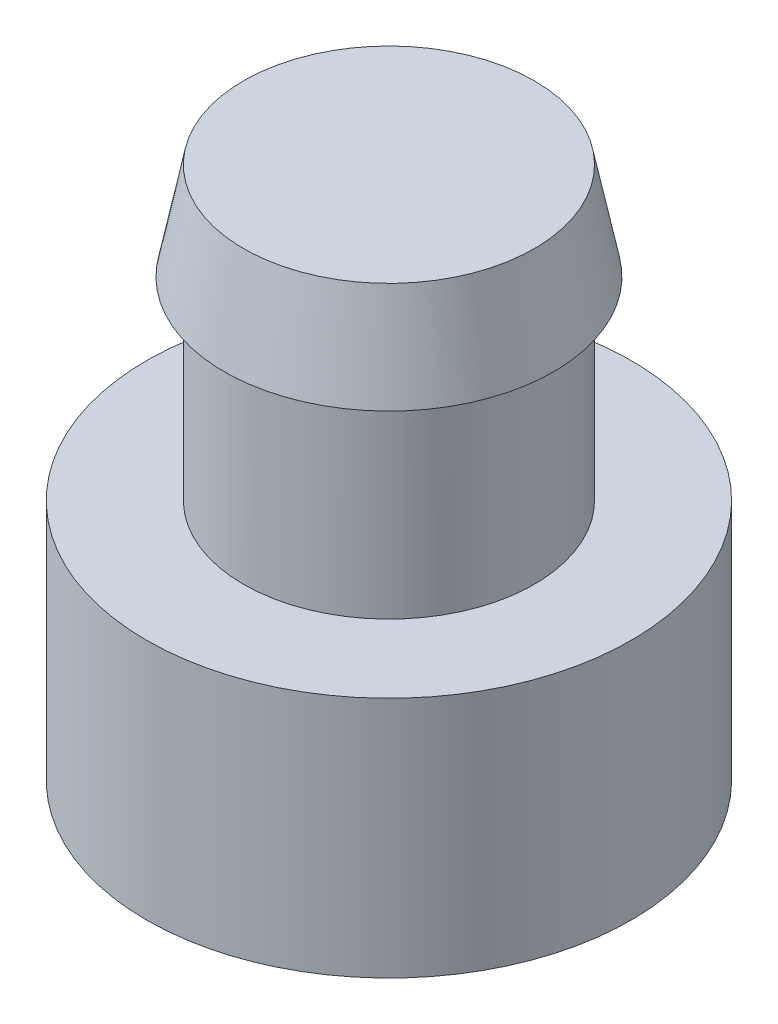
SolidWorks part; units mm, degrees
ref_plane "Front Plane" through (0, 0, 0) normal (0, 0, 1) x (1, 0, 0)
ref_plane "Top Plane" through (0, 0, 0) normal (0, 1, 0) x (1, 0, 0)
ref_plane "Right Plane" through (0, 0, 0) normal (1, 0, 0) x (0, 0, -1)
sketch "Sketch1" plane through (0, 0, 0) normal (0, 1, 0) x (1, 0, 0)
  circle A0 centre (0, 0) radius 2.5
  dimension "D1" = 5
extrude "Boss-Extrude1" add sketch "Sketch1" along normal blind 2.5
sketch "Sketch2" plane through (0, 2.5, 0) normal (0, 1, 0) x (1, 0, 0)
  circle A0 centre (0, 0) radius 1.5
  dimension "D1" = 3
extrude "Boss-Extrude2" add sketch "Sketch2" along normal blind 3
sketch "Sketch3" plane through (0, 0, 0) normal (0, 0, 1) x (1, 0, 0)
  line L0 (1.5, 5.5) -> (1.5, 4.5)
  line L1 (1.5, 2.5) -> (1.5, 5.5) construction
  line L2 (1.5, 4.5) -> (1.7, 4.5)
  line L3 (1.7, 4.5) -> (1.5, 5.5)
  line L4 (0, 0) -> (0, 5.5) construction
  line L5 (1.5, 5.5) -> (-1.5, 5.5) construction
  dimension "D1" = 0.2
  dimension "D2" = 1
revolve "Revolve1" add sketch "Sketch3" angle 360 about L4
